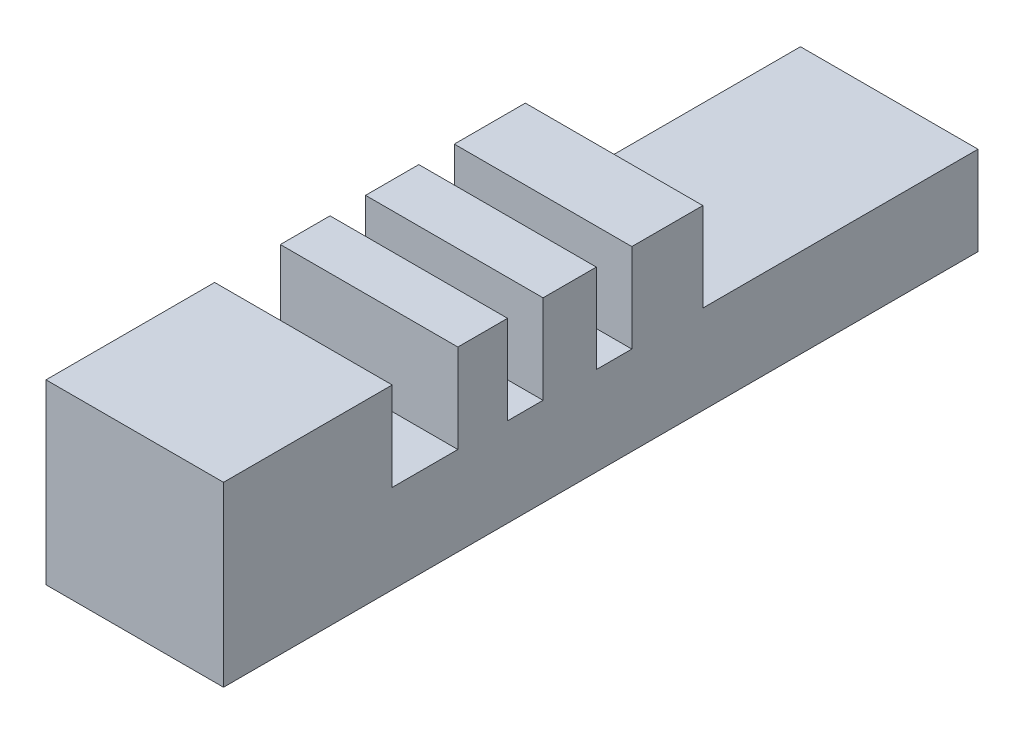
SolidWorks part; units mm, degrees
ref_plane "Front Plane" through (0, 0, 0) normal (0, 0, 1) x (1, 0, 0)
ref_plane "Top Plane" through (0, 0, 0) normal (0, 1, 0) x (1, 0, 0)
ref_plane "Right Plane" through (0, 0, 0) normal (1, 0, 0) x (0, 0, -1)
sketch "Sketch1" plane through (0, 0, 0) normal (0, 1, 0) x (1, 0, 0)
  line L0 (0, 0) -> (0, 42.5)
  line L1 (0, 42.5) -> (10, 42.5)
  line L2 (10, 42.5) -> (10, 0)
  line L3 (10, 0) -> (0, 0)
  dimension "D1" = 42.5
  dimension "D2" = 10
extrude "Boss-Extrude1" add sketch "Sketch1" along normal blind 5
sketch "Sketch2" plane through (0, 5, 0) normal (0, 1, 0) x (1, 0, 0)
  line L0 (0, 0) -> (0, 9.5)
  line L1 (0, 42.5) -> (0, 0) construction
  line L2 (0, 9.5) -> (10, 9.5)
  line L3 (10, 0) -> (10, 42.5) construction
  line L4 (10, 9.5) -> (10, 0)
  line L5 (10, 0) -> (0, 0)
  line L6 (0, 9.5) -> (0, 13.2) construction
  line L7 (0, 13.2) -> (0, 16)
  line L8 (0, 16) -> (10, 16)
  line L9 (10, 16) -> (10, 13.2)
  line L10 (10, 13.2) -> (0, 13.2)
  line L11 (0, 16) -> (0, 18)
  line L12 (0, 18) -> (0, 21)
  line L13 (0, 21) -> (10, 21)
  line L14 (10, 21) -> (10, 18)
  line L15 (10, 18) -> (0, 18)
  line L16 (0, 21) -> (0, 23) construction
  line L18 (0, 23) -> (10, 23)
  line L19 (0, 23) -> (0, 27)
  line L20 (0, 27) -> (10, 27)
  line L21 (10, 23) -> (10, 27)
  text T0 "Acrylic" font "Century Gothic" height 1.5
  text T1 "PCB" font "Century Gothic" height 1.5
  text T2 "Plate\r\n" font "Century Gothic" height 1.5
  line M1 (0, 0) -> (10, 0)
  line M2 (10, 0) -> (10, 42.5)
  line M4 (0, 42.5) -> (0, 0)
  dimension "D1" = 9.5
  dimension "D2" = 3.7
  dimension "D3" = 2.8
  dimension "D4" = 2
  dimension "D5" = 3
  dimension "D6" = 2
  dimension "D7" = 4
extrude "Boss-Extrude2" add sketch "Sketch2" along normal blind 5 contours L20 L18 M4 M2 | L15 L13 M2 M4 | L10 L8 M2 M4 | L2 M4 M1 M2
